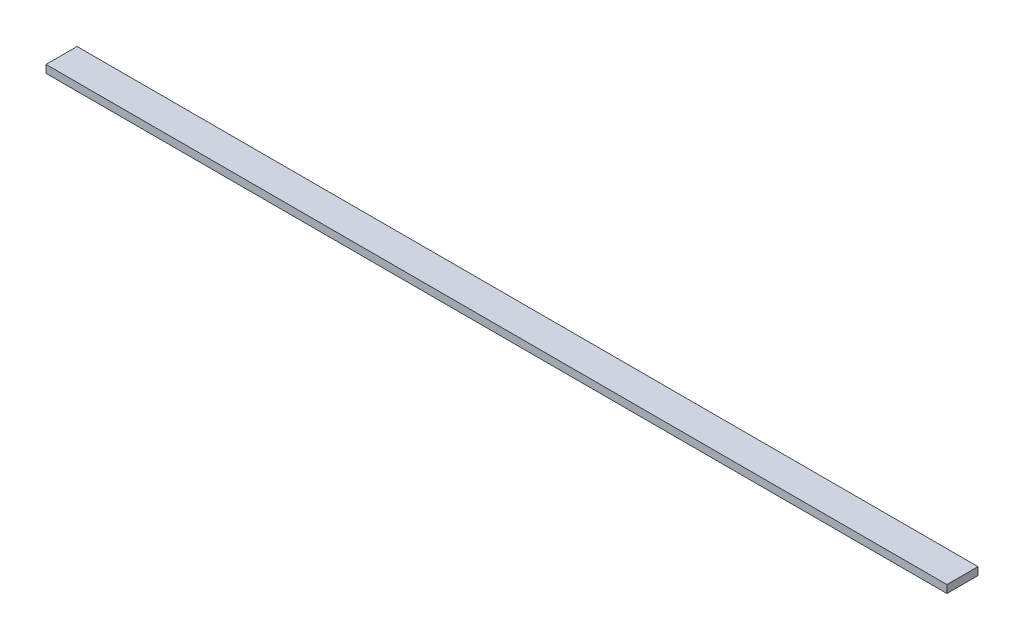
SolidWorks part; units mm, degrees
material "Rubber"
ref_plane "Front" through (0, 0, 0) normal (0, 0, 1) x (1, 0, 0)
ref_plane "Top" through (0, 0, 0) normal (0, 1, 0) x (1, 0, 0)
ref_plane "Right" through (0, 0, 0) normal (1, 0, 0) x (0, 0, -1)
sketch "Sketch1" plane through (0, 0, 0) normal (0, 1, 0) x (1, 0, 0)
  line L1 (-92.075, 3.175) -> (92.075, 3.175)
  line L2 (-92.075, 3.175) -> (-92.075, -3.175)
  line L3 (-92.075, -3.175) -> (92.075, -3.175)
  line L4 (92.075, 3.175) -> (92.075, -3.175)
  line L5 (-92.075, 3.175) -> (92.075, -3.175) construction
  line L6 (-92.075, -3.175) -> (92.075, 3.175) construction
  point P0 (0, 0)
  dimension "D1" = 184.15
  dimension "D2" = 6.35
extrude "Boss-Extrude1" add sketch "Sketch1" along normal blind 1.5875
